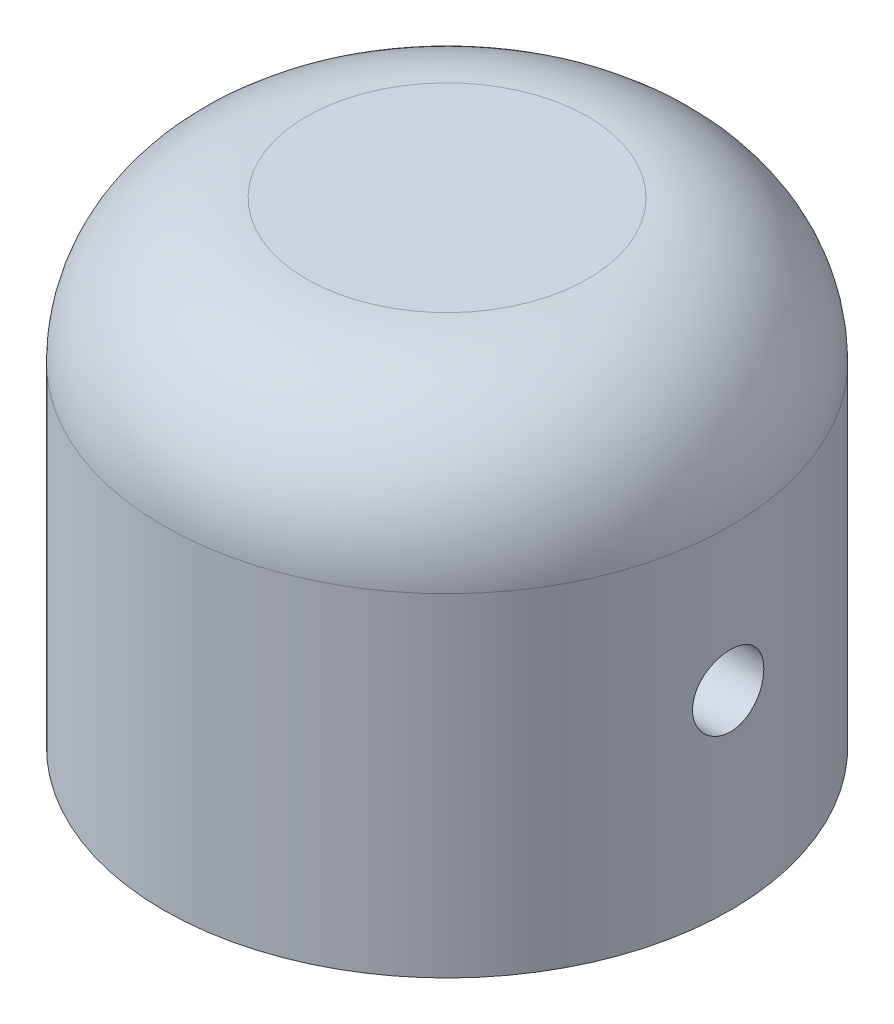
SolidWorks part; units mm, degrees
ref_plane "Front" through (0, 0, 0) normal (0, 0, 1) x (1, 0, 0)
ref_plane "Top" through (0, 0, 0) normal (0, 1, 0) x (1, 0, 0)
ref_plane "Right" through (0, 0, 0) normal (1, 0, 0) x (0, 0, -1)
sketch "Sketch1" plane through (0, 0, 0) normal (0, 1, 0) x (1, 0, 0)
  circle A0 centre (0, 0) radius 6.2865
  dimension "D1" = 12.573
extrude "Boss-Extrude1" add sketch "Sketch1" along normal blind 15.875
sketch "Sketch2" plane through (0, 0, 0) normal (0, 1, 0) x (1, 0, 0)
  circle A2 centre (0, 0) radius 9.4615
  circle A3 centre (0, 0) radius 9.4615
  dimension "D1" = 3.175
extrude "Boss-Extrude2" add sketch "Sketch2" along normal blind 15.875
sketch "Sketch3" plane through (0, 0, 0) normal (0, -1, 0) x (1, 0, 0)
  line L0 (4.889, -4.2484) -> (4.889, 4.2484)
  arc A0 (4.889, 4.2484) -> (4.889, -4.2484) centre (0, 0) ccw
  arc A1 (4.889, -4.2484) -> (4.889, 4.2484) centre (0, 0) ccw construction
  point P4 (6.477, 0)
  dimension "D1" = 6.477
  dimension "D2" = 1.588
extrude "Cut-Extrude1" cut sketch "Sketch3" against normal blind 12.7
fillet "Fillet1" radius 4.7625 1 edges at (0, 15.875, 9.4615)
sketch "Sketch4" plane through (4.889, 0, 0) normal (-1, 0, 0) x (0, 0, 1)
  line L0 (-9.4615, 0) -> (9.4615, 0) construction
  circle A0 centre (0, 6.35) radius 1.1905
  dimension "D1" = 2.381
  dimension "D2" = 6.35
extrude "Cut-Extrude2" cut sketch "Sketch4" against normal through all
